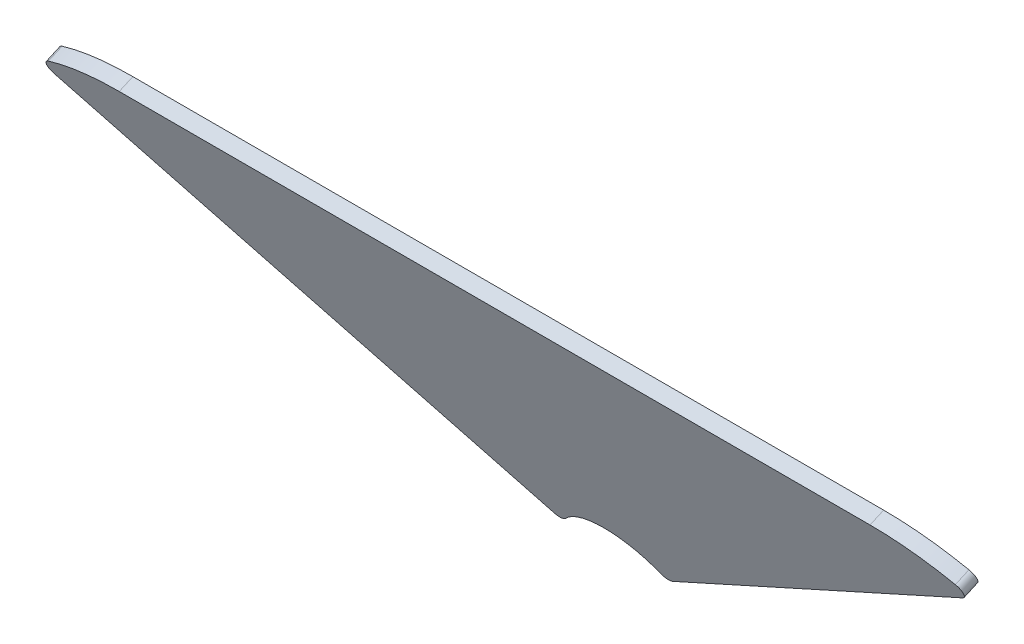
SolidWorks part; units mm, degrees
ref_plane "Front Plane" through (0, 0, 0) normal (0, 0, 1) x (1, 0, 0)
ref_plane "Top Plane" through (0, 0, 0) normal (0, 1, 0) x (1, 0, 0)
ref_plane "Right Plane" through (0, 0, 0) normal (1, 0, 0) x (0, 0, -1)
sketch "Sketch2" plane through (809.076, 0, 0) normal (1, 0, 0) x (0, 0, -1)
  line L0 (-1284.1891, 940.9723) -> (-1278.3905, 943.5604)
  line L1 (-1278.3905, 943.5604) -> (-1225.7095, 825.5286)
  circle A1 centre (-1295.7864, 935.7961) radius 12.7 construction
  spline S3 degree 3 poles (-1233.7938, 829.4131) (-1234.7457, 829.336) (-1235.3728, 829.2454) (-1236.3035, 829.0569) (-1236.6121, 828.9852) (-1237.2257, 828.8238) (-1237.5303, 828.7342) (-1238.419, 828.444) (-1238.9856, 828.2209) (-1239.7981, 827.8392) (-1240.0637, 827.7033) (-1240.5738, 827.4192) (-1240.8191, 827.2706) (-1241.5263, 826.804) (-1241.9601, 826.4656) (-1242.7478, 825.7216) (-1243.0922, 825.3244) (-1243.673, 824.4789) (-1243.9112, 824.0289) (-1244.2659, 823.0632) (-1244.3756, 822.5663) (-1244.4369, 821.7964) (-1244.4401, 821.5358) (-1244.41, 821.0056) (-1244.3762, 820.7348) (-1244.2219, 819.9318) (-1244.0491, 819.4025) (-1243.6877, 818.6182) (-1243.5494, 818.3577) (-1243.2457, 817.8524) (-1243.0797, 817.6063) (-1242.7209, 817.1266) (-1242.5281, 816.8931) (-1242.1161, 816.439) (-1241.897, 816.2187) (-1241.2141, 815.5901) (-1240.7211, 815.2089) (-1239.9274, 814.6949) (-1239.6528, 814.5329) (-1239.0947, 814.2343) (-1238.8103, 814.097) (-1237.9413, 813.7213) (-1237.3409, 813.5187) (-1236.0947, 813.2204) (-1235.4644, 813.1289) (-1234.2023, 813.0685) (-1233.5671, 813.0993) (-1232.2961, 813.2993) (-1231.6835, 813.4648) (-1230.7985, 813.8097) (-1230.5092, 813.9408) (-1229.9422, 814.2362) (-1229.6642, 814.4009) (-1228.869, 814.9315) (-1228.3824, 815.3372) (-1227.7142, 816.0178) (-1227.5013, 816.2577) (-1227.1048, 816.7507) (-1226.9199, 817.0048) (-1226.5759, 817.5272) (-1226.4167, 817.7955) (-1226.1235, 818.3454) (-1225.9889, 818.6287) (-1225.6299, 819.4829) (-1225.4481, 820.0594) (-1225.1945, 821.2216) (-1225.1234, 821.8122) (-1225.0987, 822.9487) (-1225.1429, 823.5001) (-1225.2956, 824.3005) (-1225.3613, 824.5629) (-1225.5189, 825.0665) (-1225.6109, 825.3094) (-1225.8214, 825.7777) (-1225.9399, 826.0033) (-1226.2036, 826.4372) (-1226.3499, 826.6467) (-1226.8225, 827.2389) (-1227.1821, 827.587) (-1227.9928, 828.1988) (-1228.4483, 828.4631) (-1229.4202, 828.8912) (-1229.94, 829.0586) (-1230.7768, 829.2439) (-1231.0653, 829.2944) (-1231.6483, 829.3719) (-1231.9446, 829.3993) (-1232.5471, 829.4324) (-1232.8532, 829.4382) (-1233.476, 829.4286) (-1233.7938, 829.4131) (-1234.7457, 829.336) (-1235.3728, 829.2454) knots -0.015625 -0.015625 0 0 0.03125 0.03125 0.046875 0.046875 0.0625 0.0625 0.09375 0.09375 0.109375 0.109375 0.125 0.125 0.15625 0.15625 0.1875 0.1875 0.21875 0.21875 0.25 0.25 0.265625 0.265625 0.28125 0.28125 0.3125 0.3125 0.328125 0.328125 0.34375 0.34375 0.359375 0.359375 0.375 0.375 0.40625 0.40625 0.421875 0.421875 0.4375 0.4375 0.46875 0.46875 0.5 0.5 0.53125 0.53125 0.5625 0.5625 0.578125 0.578125 0.59375 0.59375 0.625 0.625 0.640625 0.640625 0.65625 0.65625 0.671875 0.671875 0.6875 0.6875 0.71875 0.71875 0.75 0.75 0.78125 0.78125 0.796875 0.796875 0.8125 0.8125 0.828125 0.828125 0.84375 0.84375 0.875 0.875 0.90625 0.90625 0.9375 0.9375 0.953125 0.953125 0.96875 0.96875 0.984375 0.984375 1 1 1.03125 1.03125 1.046875 only from (-1234.1111, 829.3874) to (-1234.1111, 829.3874) construction
  point P4 (-1295.7864, 935.7961)
  dimension "D1" = 6.35
ref_plane "Plane1" through (809.076, 943.5604, 1278.3905) normal (0, 0.4076, -0.9132) x (-1, 0, 0)
sketch "Sketch3" plane through (809.076, 943.5604, 1278.3905) normal (0, 0.4076, -0.9132) x (-1, 0, 0)
  line L0 (172.3646, -121.5239) -> (336.0742, -14.5067)
  line L1 (172.3646, -121.5239) -> (336.0742, -14.5067) construction
  line L2 (320.1984, -12.7) -> (0, -12.7)
  line L3 (320.1984, -12.7) -> (0, -12.7) construction
  line L4 (-15.876, -14.5065) -> (147.8319, -121.5225)
  line L5 (-15.876, -14.5065) -> (147.8319, -121.5225) construction
  line L6 (138.0464, -137.8726) -> (138.0314, -137.8743)
  line L7 (138.0464, -137.8726) -> (138.0314, -137.8743) construction
  line L8 (138.0314, -137.8743) -> (-37.1352, -23.3686)
  line L9 (138.0314, -137.8743) -> (-37.1352, -23.3686) construction
  line L10 (0, 12.7) -> (320.1984, 12.7)
  line L11 (0, 12.7) -> (320.1984, 12.7) construction
  line L12 (357.3336, -23.3686) -> (182.167, -137.8743)
  line L13 (357.3336, -23.3686) -> (182.167, -137.8743) construction
  line L14 (182.167, -137.8743) -> (182.1561, -137.8756)
  line L15 (182.167, -137.8743) -> (182.1561, -137.8756) construction
  line L16 (-37.1352, -23.3686) -> (-15.876, -14.5065) construction
  line L17 (0, 12.7) -> (0, -12.7) construction
  line L18 (320.1984, 12.7) -> (320.1984, -12.7) construction
  line L19 (177.1127, -118.42) -> (187.5358, -134.3648) construction
  line L20 (143.0858, -118.42) -> (132.6627, -134.3648) construction
  line L21 (336.0742, -14.5067) -> (357.3336, -23.3686) construction
  line L22 (147.8319, -121.5225) -> (172.3646, -121.5239) construction
  line L23 (137.8743, -126.3924) -> (-26.5056, -18.9376)
  line L24 (-26.5056, -18.9376) -> (-39.0764, -10.7201)
  line L25 (-39.0764, -10.7201) -> (-51.6473, -2.5025) construction
  line L26 (182.3243, -126.3924) -> (346.7039, -18.9376)
  line L27 (346.7039, -18.9376) -> (359.2746, -10.7202)
  line L28 (359.2746, -10.7202) -> (371.8453, -2.5027) construction
  line L29 (320.1984, 0) -> (0, 0)
  arc A1 (0, 0) -> (-39.0764, -10.7201) centre (0, -76.5802) ccw
  arc A2 (320.1984, 0) -> (359.2746, -10.7202) centre (320.1984, -76.5785) cw
  arc A3 (182.3243, -126.3924) -> (137.8743, -126.3924) centre (160.0993, -140.9209) ccw
  spline S0 degree 3 poles (1472.3787, 4851.1722) (439.0724, -119.1011) (394.2576, -25.3982) (332.152, -13.7071) (330.1746, -13.3955) (328.189, -13.1412) (326.1969, -12.9437) (324.2, -12.8033) (322.5333, -12.735) (263.8888, -11.5692) (204.9419, -63.7887) (249.4024, 4983.6661) knots -11.464584 -11.464584 -11.464584 -11.464584 0.125 0.25 0.375 0.5 0.625 0.75 0.875 0.9375 11.73936 11.73936 11.73936 11.73936 only from (336.0742, -14.5067) to (320.1984, -12.7)
  spline S1 degree 3 poles (336.0742, -14.5067) (335.4229, -14.3617) (334.1191, -14.0774) (332.152, -13.7071) (330.1746, -13.3955) (328.189, -13.1412) (326.1969, -12.9437) (324.2, -12.8033) (322.5333, -12.735) (321.1992, -12.7085) (320.532, -12.7023) (320.1984, -12.7) knots 0 0 0 0 0.125 0.25 0.375 0.5 0.625 0.75 0.875 0.9375 1 1 1 1 construction
  spline S2 degree 3 poles (7.957, 4984.0871) (119.2318, -89.2229) (56.9052, -10.2663) (-4.0017, -12.8042) (-5.9986, -12.9444) (-7.9907, -13.1418) (-9.9764, -13.3957) (-11.6242, -13.6549) (-12.9375, -13.8912) (-13.9198, -14.0829) (-14.7359, -14.2548) (-68.1042, -25.9691) (-116.0829, -61.5494) (-1208.0334, 4838.4634) knots -11.044699 -11.044699 -11.044699 -11.044699 0.125 0.25 0.375 0.5 0.625 0.75 0.8125 0.875 0.9375 0.96875 11.111473 11.111473 11.111473 11.111473 only from (0, -12.7) to (-15.876, -14.5065)
  spline S3 degree 3 poles (0, -12.7) (-0.6672, -12.7052) (-2.0016, -12.7208) (-4.0017, -12.8042) (-5.9986, -12.9444) (-7.9907, -13.1418) (-9.9764, -13.3957) (-11.6242, -13.6549) (-12.9375, -13.8912) (-13.9198, -14.0829) (-14.7359, -14.2548) (-15.3876, -14.3978) (-15.7132, -14.4702) (-15.876, -14.5065) knots 0 0 0 0 0.125 0.25 0.375 0.5 0.625 0.75 0.8125 0.875 0.9375 0.96875 1 1 1 1 construction
  spline S4 degree 3 poles (4194.7578, 2814.3152) (100.4338, -146.6367) (145.359, -118.4519) (147.9521, -121.6506) (147.9886, -121.7436) (148.0023, -121.8435) (148.0029, -121.9453) (147.9576, -122.2239) (147.6475, -122.8215) (147.03, -123.6162) (146.3619, -124.385) (145.8261, -124.9925) (144.4792, -126.5046) (142.2445, -129.1324) (140.3076, -132.2435) (139.2712, -134.4416) (138.8866, -135.3781) (138.6085, -136.1385) (138.4158, -136.7147) (138.2644, -137.1982) (136.1588, -144.9962) (115.2862, -144.7066) (-4373.1837, 2017.4568) knots -0.628995 -0.628995 -0.628995 -0.628995 0.003906 0.007812 0.015625 0.019531 0.023438 0.03125 0.0625 0.125 0.1875 0.21875 0.25 0.5 0.75 0.8125 0.875 0.90625 0.9375 0.96875 0.984375 2.176145 2.176145 2.176145 2.176145 only from (147.8319, -121.5225) to (138.0464, -137.8726)
  spline S5 degree 3 poles (147.8319, -121.5225) (147.8514, -121.539) (147.8892, -121.5731) (147.9521, -121.6506) (147.9886, -121.7436) (148.0023, -121.8435) (148.0029, -121.9453) (147.9576, -122.2239) (147.6475, -122.8215) (147.03, -123.6162) (146.3619, -124.385) (145.8261, -124.9925) (144.4792, -126.5046) (142.2445, -129.1324) (140.3076, -132.2435) (139.2712, -134.4416) (138.8866, -135.3781) (138.6085, -136.1385) (138.4158, -136.7147) (138.2644, -137.1982) (138.1582, -137.5916) (138.0924, -137.7831) (138.0464, -137.8726) knots 0 0 0 0 0.003906 0.007812 0.015625 0.019531 0.023438 0.03125 0.0625 0.125 0.1875 0.21875 0.25 0.5 0.75 0.8125 0.875 0.90625 0.9375 0.96875 0.984375 1 1 1 1 construction
  spline S6 degree 3 poles (-2802.462, 4137.0211) (151.5821, -51.4057) (17.2327, 16.2461) (-41.1486, -26.1257) (-42.4376, -27.1129) (-43.7014, -28.132) (-45.3518, -29.5327) (-47.3472, -31.3613) (-49.6253, -33.6762) (-52.4979, -36.9167) (-55.7604, -41.2434) (-58.5364, -45.8978) (-60.4394, -49.788) (-61.7017, -52.7808) (-62.7938, -55.8399) (-63.5582, -58.4364) (-64.0794, -60.5374) (-64.4233, -62.1239) (-75.1577, -120.2239) (-3.0667, -192.2654) (-5010.7909, 647.8455) knots -4.040732 -4.040732 -4.040732 -4.040732 0.0625 0.09375 0.125 0.15625 0.1875 0.25 0.3125 0.375 0.5 0.625 0.6875 0.75 0.8125 0.875 0.90625 0.9375 0.96875 4.318501 4.318501 4.318501 4.318501 only from (-37.1352, -23.3686) to (-64.9679, -65.3243)
  spline S7 degree 3 poles (-37.1352, -23.3686) (-38.0436, -23.9571) (-39.3968, -24.8542) (-41.1486, -26.1257) (-42.4376, -27.1129) (-43.7014, -28.132) (-45.3518, -29.5327) (-47.3472, -31.3613) (-49.6253, -33.6762) (-52.4979, -36.9167) (-55.7604, -41.2434) (-58.5364, -45.8978) (-60.4394, -49.788) (-61.7017, -52.7808) (-62.7938, -55.8399) (-63.5582, -58.4364) (-64.0794, -60.5374) (-64.4233, -62.1239) (-64.7183, -63.7201) (-64.8866, -64.7893) (-64.9679, -65.3243) knots 0 0 0 0 0.0625 0.09375 0.125 0.15625 0.1875 0.25 0.3125 0.375 0.5 0.625 0.6875 0.75 0.8125 0.875 0.90625 0.9375 0.96875 1 1 1 1 construction
  spline S8 degree 3 poles (-79.7634, -58.9136) (-71.7966, -59.4027) (252.4469, -114.9858) (-78.1684, -67.9546) (-574.4838, 2.648) (-81.459, -58.0175) (-73.9171, -59.7626) knots -1.818975 -1.818975 -1.818975 -1.818975 0.5 0.5 0.5 2.885523 2.885523 2.885523 2.885523 weights 11.00192 3.417531 0.083557 1 0.057258 3.612381 11.665369 only from (-64.9679, -65.3243) to (-90.1135, -61.7473)
  spline S9 degree 3 poles (-64.9679, -65.3243) (-65.2615, -67.9179) (-70.7453, -69.0106) (-78.1684, -67.9546) (-85.5916, -66.8986) (-90.5538, -64.32) (-90.1135, -61.7473) knots 0 0 0 0 0.5 0.5 0.5 1 1 1 1 weights 1 0.802404 0.802404 1 0.802404 0.802404 1 construction
  spline S10 degree 3 poles (-5048.1997, 557.1323) (-61.6212, -184.2849) (-99.2135, -118.4436) (-89.7553, -59.4524) (-89.4623, -57.8194) (-89.0621, -55.8692) (-88.1658, -51.9897) (-85.711, -43.7116) (-77.8969, -26.7498) (-63.7471, -10.4447) (-46.0277, 1.4017) (-33.8524, 6.8052) (-23.6716, 9.8521) (-15.8721, 11.4935) (-9.2813, 12.3124) (80.7247, 18.038) (173.1235, -114.2911) (-45.2928, 5006.1324) knots -1.375475 -1.375475 -1.375475 -1.375475 0.007812 0.015625 0.03125 0.046875 0.0625 0.125 0.25 0.5 0.625 0.75 0.8125 0.875 0.9375 0.96875 2.997946 2.997946 2.997946 2.997946 only from (-90.1135, -61.7473) to (0, 12.7)
  spline S11 degree 3 poles (-90.1135, -61.7473) (-90.0645, -61.4191) (-89.9654, -60.7629) (-89.7553, -59.4524) (-89.4623, -57.8194) (-89.0621, -55.8692) (-88.1658, -51.9897) (-85.711, -43.7116) (-77.8969, -26.7498) (-63.7471, -10.4447) (-46.0277, 1.4017) (-33.8524, 6.8052) (-23.6716, 9.8521) (-15.8721, 11.4935) (-9.2813, 12.3124) (-3.9817, 12.6495) (-1.3272, 12.6912) (0, 12.7) knots 0 0 0 0 0.007812 0.015625 0.03125 0.046875 0.0625 0.125 0.25 0.5 0.625 0.75 0.8125 0.875 0.9375 0.96875 1 1 1 1 construction
  spline S12 degree 3 poles (4494.1762, -2544.9815) (-337.5044, -615.7094) (160.8261, 113.9869) (380.4045, -6.3698) (398.0978, -26.7476) (405.9099, -43.7122) (408.3644, -51.9879) (409.2602, -55.8692) (409.6604, -57.8196) (409.9533, -59.4525) (419.4583, -118.7012) (382.4457, -184.8082) (5367.0021, 565.4115) knots -5.058262 -5.058262 -5.058262 -5.058262 0.25 0.5 0.75 0.875 0.9375 0.953125 0.96875 0.984375 0.992188 2.381668 2.381668 2.381668 2.381668 only from (320.1984, 12.7) to (410.3119, -61.7473)
  spline S13 degree 3 poles (320.1984, 12.7) (330.8167, 12.6954) (352.0512, 9.1714) (380.4045, -6.3698) (398.0978, -26.7476) (405.9099, -43.7122) (408.3644, -51.9879) (409.2602, -55.8692) (409.6604, -57.8196) (409.9533, -59.4525) (410.1635, -60.7629) (410.2628, -61.4191) (410.3119, -61.7473) knots 0 0 0 0 0.25 0.5 0.75 0.875 0.9375 0.953125 0.96875 0.984375 0.992188 1 1 1 1 construction
  spline S14 degree 3 poles (394.2955, -59.7215) (402.0567, -57.9701) (741.2926, -19.1722) (398.3668, -67.9546) (90.7573, -111.7131) (391.896, -59.4198) (399.9154, -58.9165) knots -1.825952 -1.825952 -1.825952 -1.825952 0.5 0.5 0.5 2.804574 2.804574 2.804574 2.804574 weights 11.070489 3.43763 0.0808 1 0.089249 3.376284 10.861105 only from (410.3119, -61.7473) to (385.1663, -65.3243)
  spline S15 degree 3 poles (410.3119, -61.7473) (410.7522, -64.32) (405.79, -66.8986) (398.3668, -67.9546) (390.9437, -69.0106) (385.4599, -67.9179) (385.1663, -65.3243) knots 0 0 0 0 0.5 0.5 0.5 1 1 1 1 weights 1 0.802404 0.802404 1 0.802404 0.802404 1 construction
  spline S16 degree 3 poles (5330.1232, 652.8729) (319.8415, -197.2801) (395.7307, -122.3187) (384.5235, -61.5918) (383.9094, -58.9558) (382.9915, -55.8399) (380.8083, -49.7213) (377.2644, -42.9734) (372.0436, -36.0516) (368.3434, -32.0932) (365.1513, -29.1668) (362.6493, -27.0957) (301.721, 18.3307) (160.8076, -52.6422) (3145.577, 4121.3269) knots -3.441467 -3.441467 -3.441467 -3.441467 0.03125 0.0625 0.125 0.1875 0.25 0.5 0.625 0.75 0.8125 0.875 0.9375 5.199975 5.199975 5.199975 5.199975 only from (385.1663, -65.3243) to (357.3336, -23.3686)
  spline S17 degree 3 poles (385.1663, -65.3243) (385.0851, -64.7892) (384.9163, -63.7202) (384.5235, -61.5918) (383.9094, -58.9558) (382.9915, -55.8399) (380.8083, -49.7213) (377.2644, -42.9734) (372.0436, -36.0516) (368.3434, -32.0932) (365.1513, -29.1668) (362.6493, -27.0957) (360.0455, -25.1544) (358.2421, -23.9569) (357.3336, -23.3686) knots 0 0 0 0 0.03125 0.0625 0.125 0.1875 0.25 0.5 0.625 0.75 0.8125 0.875 0.9375 1 1 1 1 construction
  spline S18 degree 3 poles (4060.0597, 3017.5541) (322.7121, -86.9076) (185.2022, -147.7512) (182.0433, -137.5958) (181.9995, -137.4497) (181.9556, -137.3037) (181.8822, -137.0607) (181.7629, -136.6733) (181.5887, -136.1444) (181.3825, -135.5732) (181.1605, -135.008) (180.8445, -134.2625) (180.2409, -132.9798) (179.4453, -131.5658) (178.5634, -130.2047) (177.8635, -129.2095) (177.13, -128.2383) (176.3678, -127.2894) (175.7132, -126.5151) (175.181, -125.9031) (174.6445, -125.2951) (174.1039, -124.6908) (173.5697, -124.0807) (173.2425, -123.6936) (172.9885, -123.3776) (172.8035, -123.1362) (172.6263, -122.8888) (172.461, -122.633) (172.3399, -122.409) (172.2604, -122.2204) (172.2152, -122.0737) (172.1916, -121.922) (172.1994, -121.7953) (172.2283, -121.7007) (172.2626, -121.6352) (174.9605, -118.258) (217.6217, -141.0682) (-4019.0172, 2603.2457) knots -1.609062 -1.609062 -1.609062 -1.609062 0.007812 0.015625 0.023438 0.03125 0.039062 0.0625 0.09375 0.125 0.15625 0.1875 0.25 0.375 0.4375 0.5 0.5625 0.625 0.6875 0.71875 0.75 0.8125 0.84375 0.875 0.890625 0.90625 0.921875 0.9375 0.953125 0.960938 0.96875 0.976562 0.984375 0.988281 0.992188 0.996094 1.665013 1.665013 1.665013 1.665013 only from (182.1561, -137.8756) to (172.3646, -121.5239)
  spline S19 degree 3 poles (182.1561, -137.8756) (182.1313, -137.8323) (182.0886, -137.7416) (182.0433, -137.5958) (181.9995, -137.4497) (181.9556, -137.3037) (181.8822, -137.0607) (181.7629, -136.6733) (181.5887, -136.1444) (181.3825, -135.5732) (181.1605, -135.008) (180.8445, -134.2625) (180.2409, -132.9798) (179.4453, -131.5658) (178.5634, -130.2047) (177.8635, -129.2095) (177.13, -128.2383) (176.3678, -127.2894) (175.7132, -126.5151) (175.181, -125.9031) (174.6445, -125.2951) (174.1039, -124.6908) (173.5697, -124.0807) (173.2425, -123.6936) (172.9885, -123.3776) (172.8035, -123.1362) (172.6263, -122.8888) (172.461, -122.633) (172.3399, -122.409) (172.2604, -122.2204) (172.2152, -122.0737) (172.1916, -121.922) (172.1994, -121.7953) (172.2283, -121.7007) (172.2626, -121.6352) (172.3093, -121.5768) (172.3458, -121.5413) (172.3646, -121.5239) knots 0 0 0 0 0.007812 0.015625 0.023438 0.03125 0.039062 0.0625 0.09375 0.125 0.15625 0.1875 0.25 0.375 0.4375 0.5 0.5625 0.625 0.6875 0.71875 0.75 0.8125 0.84375 0.875 0.890625 0.90625 0.921875 0.9375 0.953125 0.960938 0.96875 0.976562 0.984375 0.988281 0.992188 0.996094 1 1 1 1 construction
  point P22 (0, 0)
  point P23 (-26.5056, -18.9376)
  point P25 (137.8743, -126.3924)
  point P26 (320.1984, 0)
  point P27 (346.7037, -18.9376)
  point P28 (182.3243, -126.3924)
  point P31 (160.0982, -121.5232)
  point P32 (160.0982, -121.5232)
  dimension "D1" = 44.45
extrude "Boss-Extrude1" add sketch "Sketch3" along normal blind 6.35
fillet "Fillet1" radius 3.81 4 edges at (671.2018, 829.4365, 1223.9768) (626.7518, 829.4365, 1223.9768) (449.8014, 935.0651, 1271.1219) (848.1525, 935.0652, 1271.1219)
